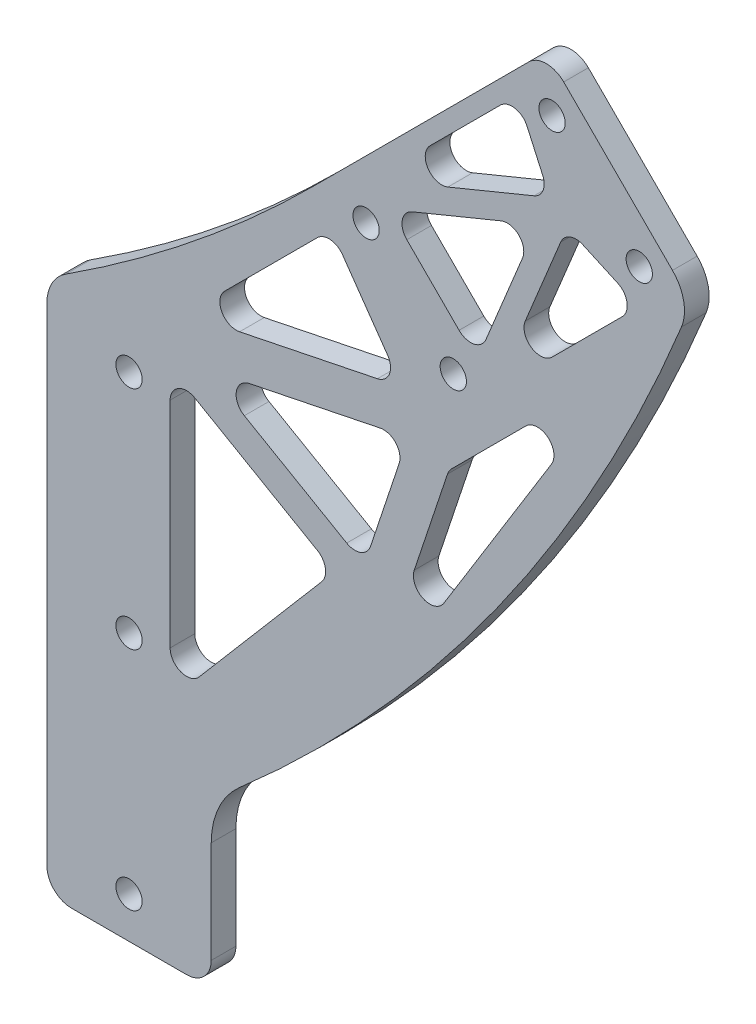
SolidWorks part; units mm, degrees
ref_plane "前视基准面" through (0, 0, 0) normal (0, 0, 1) x (1, 0, 0)
ref_plane "上视基准面" through (0, 0, 0) normal (0, 1, 0) x (1, 0, 0)
ref_plane "右视基准面" through (0, 0, 0) normal (1, 0, 0) x (0, 0, -1)
other "Configuration Table"
sketch "草图1" plane through (0, 0, 0) normal (0, 0, 1) x (1, 0, 0)
  line L1 (0, 0) -> (20, 0)
  line L2 (0, 0) -> (0, 65)
  line L3 (0, 65) -> (20, 65)
  line L4 (20, 0) -> (20, 65)
  dimension "D1" = 20
  dimension "D2" = 65
extrude "凸台-拉伸1" add sketch "草图1" along normal blind 3
sketch "草图2" plane through (0, 0, 3) normal (0, 0, 1) x (1, 0, 0)
  line L0 (10, 65) -> (10, 0) construction
  line L1 (20, 65) -> (0, 65) construction
  line L2 (0, 0) -> (20, 0) construction
  circle A0 centre (10, 60) radius 1.6
  circle A1 centre (10, 32.5) radius 1.6
  circle A2 centre (10, 5) radius 1.6
  dimension "D1" = 3.2
  dimension "D2" = 27.5
  dimension "D3" = 27.5
  dimension "D4" = 5
extrude "切除-拉伸1" cut sketch "草图2" against normal blind 3
sketch "草图3" plane through (0, 0, 3) normal (0, 0, 1) x (1, 0, 0)
  line L0 (-40, 32.5) -> (25.4074, 97.9074) construction
  line L1 (-40, 32.5) -> (8.4, 32.5) construction
  line L2 (43.085, 80.2297) -> (71.3693, 108.514) construction
  line L3 (25.4074, 97.9074) -> (43.085, 80.2297) construction
  line L4 (32.4784, 90.8363) -> (50.1561, 73.1586)
  line L6 (50.1561, 73.1586) -> (78.4404, 101.4429)
  line L7 (78.4404, 101.4429) -> (60.7627, 119.1206)
  line L8 (60.7627, 119.1206) -> (32.4784, 90.8363)
  circle A0 centre (-40, 32.5) radius 92.5 construction
  circle A1 centre (10, 60) radius 1.6 construction
  circle A2 centre (10, 32.5) radius 1.6 construction
  dimension "D3" = 185
  dimension "D5" = 25
  dimension "D6" = 40
  dimension "D1" = 50
  dimension "D2" = 27.5
  dimension "D4" = 45
  dimension "D7" = 10
  dimension "D8" = 15
extrude "凸台-拉伸2" add sketch "草图3" against normal blind 3 separate body
sketch "草图4" plane through (0, 0, 3) normal (0, 0, 1) x (1, 0, 0)
  line L0 (20, 0) -> (20, 20) construction
  line L1 (20, 0) -> (20, 65) construction
  line L2 (60.7627, 119.1206) -> (32.4784, 90.8363) construction
  line L3 (50.1561, 73.1586) -> (78.4404, 101.4429) construction
  line L4 (32.4784, 90.8363) -> (50.1561, 73.1586) construction
  line L5 (20, 65) -> (0, 65) construction
  line L6 (50.1561, 73.1586) -> (78.4404, 101.4429)
  line L7 (32.4784, 90.8363) -> (50.1561, 73.1586)
  line L8 (20, 0) -> (20, 65)
  line L9 (20, 65) -> (0, 65)
  arc A0 (32.4784, 90.8363) -> (0, 65) centre (-97.176, 220.4907) cw
  arc A1 (20, 20) -> (78.4404, 101.4429) centre (-108.0891, 173.6007) ccw
  line M9 (32.4784, 90.8363) -> (50.1561, 73.1586)
  line M10 (50.1561, 73.1586) -> (78.4404, 101.4429)
  dimension "D1" = 20
  dimension "D2" = 200
extrude "凸台-拉伸3" add sketch "草图4" against normal blind 3 contours L8 A1 A0 L9 M10 M9
sketch "草图7" plane through (0, 0, 3) normal (0, 0, 1) x (1, 0, 0)
  line L0 (60.7627, 119.1206) -> (67.8338, 112.0495) construction
  line L1 (78.4404, 101.4429) -> (60.7627, 119.1206) construction
  line L2 (67.8338, 112.0495) -> (39.5495, 83.7652) construction
  circle A0 centre (64.2983, 108.514) radius 1.6
  circle A1 centre (55.813, 100.0287) radius 1.6
  circle A2 centre (47.3277, 91.5434) radius 1.6
  dimension "D3" = 3.2
  dimension "D4" = 5
  dimension "D5" = 12
  dimension "D6" = 12
  dimension "D1" = 40
  dimension "D2" = 10
extrude "切除-拉伸2" [suppressed] cut sketch "草图7" against normal blind 3
sketch "草图8" plane through (0, 0, 3) normal (0, 0, 1) x (1, 0, 0)
  line L0 (61.4698, 112.7566) -> (38.8424, 90.1292) construction
  line L1 (38.8424, 90.1292) -> (49.449, 79.5226) construction
  line L2 (49.449, 79.5226) -> (72.0764, 102.15) construction
  line L3 (72.0764, 102.15) -> (61.4698, 112.7566) construction
  line L4 (78.4404, 101.4429) -> (60.7627, 119.1206) construction
  line L5 (60.7627, 119.1206) -> (32.4784, 90.8363) construction
  line L6 (-40, 32.5) -> (25.4074, 97.9074) construction
  line L7 (78.4404, 101.4429) -> (60.7627, 119.1206) construction
  circle A0 centre (61.4698, 112.7566) radius 1.6
  circle A1 centre (72.0764, 102.15) radius 1.6
  circle A2 centre (49.449, 79.5226) radius 1.6
  circle A3 centre (38.8424, 90.1292) radius 1.6
  dimension "D5" = 3.2
  dimension "D1" = 15
  dimension "D2" = 32
  dimension "D3" = 15
  dimension "D4" = 4
extrude "切除-拉伸3" cut sketch "草图8" against normal through all
fillet "圆角1" radius 10 1 edges at (20, 20, 1.5)
fillet "圆角2" radius 3 3 edges at (60.7627, 119.1206, 1.5) (0, 0, 1.5) (20, 0, 1.5)
fillet "圆角3" radius 5 2 edges at (78.4404, 101.4429, 1.5) (0, 65, 1.5)
sketch "草图9" plane through (0, 0, 3) normal (0, 0, 1) x (1, 0, 0)
  line L0 (20, 25) -> (20, 45)
  line L1 (20, 45) -> (52.5519, 63.7939)
  line L2 (52.5519, 63.7939) -> (20, 25)
  line L3 (20, 3) -> (20, 15.3876) construction
  line L4 (3, 0) -> (17, 0) construction
  dimension "D1" = 120
  dimension "D2" = 25
  dimension "D3" = 40
  dimension "D4" = 20
sketch "草图10" plane through (0, 0, 3) normal (0, 0, 1) x (1, 0, 0)
  line L0 (16.9221, 69.6231) -> (34.5998, 87.3008)
  line L1 (34.5998, 87.3008) -> (43.2034, 75.0135)
  line L2 (43.2034, 75.0135) -> (16.9221, 69.6231)
  line L3 (19.4655, 65.0407) -> (43.9556, 70.0637)
  line L4 (43.9556, 70.0637) -> (38.6058, 53.99)
  line L5 (38.6058, 53.99) -> (19.4655, 65.0407)
  line L14 (15, 63) -> (35, 51.453)
  line L15 (35, 51.453) -> (15, 28)
  line L16 (15, 28) -> (15, 63)
  line L17 (39.5495, 95.079) -> (57.2272, 112.7566)
  line L18 (57.2272, 112.7566) -> (61.187, 103.9885)
  line L19 (61.187, 103.9885) -> (39.5495, 95.079)
  line L20 (41.6708, 92.9576) -> (59.7021, 100.3823)
  line L21 (59.7021, 100.3823) -> (52.2774, 82.351)
  line L22 (52.2774, 82.351) -> (41.6708, 92.9576)
  line L23 (38.8424, 90.1292) -> (49.449, 79.5226) construction
  line L24 (44.1457, 84.8259) -> (51.7017, 92.3819) construction
  line L25 (63.3083, 101.8672) -> (54.3988, 80.2297)
  line L26 (72.0764, 97.9074) -> (63.3083, 101.8672)
  line L27 (54.3988, 80.2297) -> (72.0764, 97.9074)
  line L28 (58.6414, 116.9993) -> (32.4784, 90.8363) construction
  line L29 (76.117, 103.7663) -> (62.884, 116.9993) construction
  line L30 (0, 62.2529) -> (0, 3) construction
  line L31 (3, 0) -> (17, 0) construction
  line L32 (48.8939, 69.068) -> (39.2814, 40.1872)
  line L33 (39.2814, 40.1872) -> (70.4172, 90.5913)
  line L34 (70.4172, 90.5913) -> (48.8939, 69.068)
  line L35 (48.8939, 69.068) -> (54.8493, 65.3892) construction
  circle A0 centre (10, 32.5) radius 1.6 construction
  dimension "D1" = 2
  dimension "D2" = 3
  dimension "D3" = 7
  dimension "D4" = 25
  dimension "D5" = 15
  dimension "D6" = 4
  dimension "D7" = 18
  dimension "D8" = 5
  dimension "D9" = 4
  dimension "D10" = 80
  dimension "D11" = 15
  dimension "D12" = 25
  dimension "D13" = 5
  dimension "D14" = 5
  dimension "D15" = 25
  dimension "D16" = 60
  dimension "D17" = 4
  dimension "D18" = 60
  dimension "D19" = 35
  dimension "D20" = 20
  dimension "D21" = 28
  dimension "D22" = 5
  dimension "D23" = 4
  dimension "D24" = 7
  dimension "D25" = 90
extrude "切除-拉伸4" cut sketch "草图10" against normal through all
fillet "圆角4" radius 2 21 edges at (16.9221, 69.6231, 1.5) (34.5998, 87.3008, 1.5) (43.2034, 75.0135, 1.5) (72.0764, 97.9074, 1.5) (54.3988, 80.2297, 1.5) (63.3083, 101.8672, 1.5) (70.4172, 90.5913, 1.5) (48.8939, 69.068, 1.5) (39.5495, 95.079, 1.5) (57.2272, 112.7566, 1.5) (61.187, 103.9885, 1.5) (41.6708, 92.9576, 1.5) (59.7021, 100.3823, 1.5) (52.2774, 82.351, 1.5) (19.4655, 65.0407, 1.5) (43.9556, 70.0637, 1.5) (38.6058, 53.99, 1.5) (15, 63, 1.5) (35, 51.453, 1.5) (15, 28, 1.5) (39.2814, 40.1872, 1.5)
